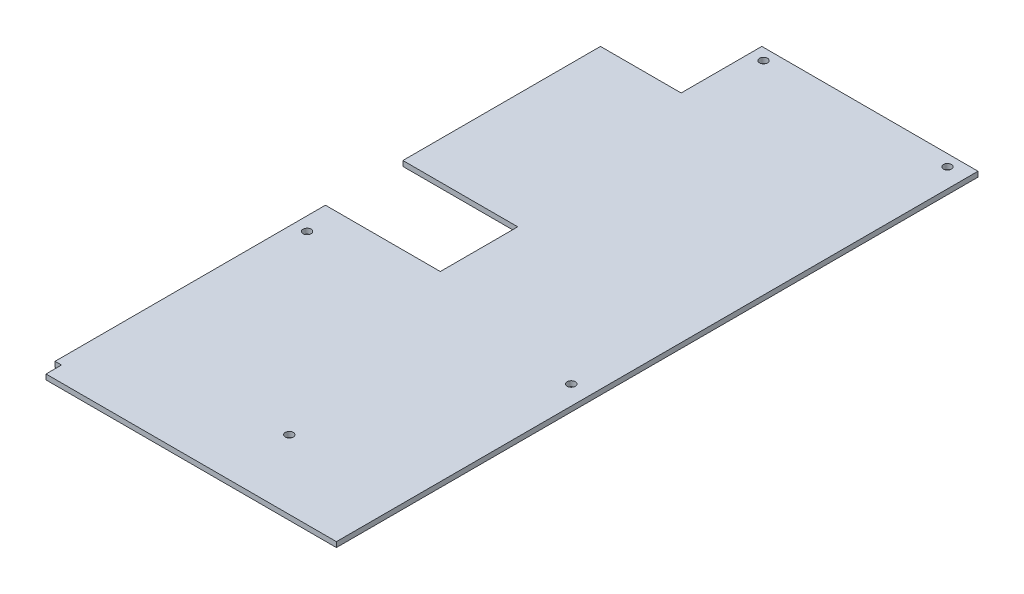
SolidWorks part; units mm, degrees
material "PBT General Purpose"
ref_plane "Front" through (0, 0, 0) normal (0, 0, 1) x (1, 0, 0)
ref_plane "Top" through (0, 0, 0) normal (0, 1, 0) x (1, 0, 0)
ref_plane "Right" through (0, 0, 0) normal (1, 0, 0) x (0, 0, -1)
other "Configuration Table"
sketch "Sketch2" plane through (0, 0, 0) normal (0, 1, 0) x (1, 0, 0)
  line L1 (0, 0) -> (93, 0)
  line L2 (0, 0) -> (0, 198.84)
  line L3 (0, 198.84) -> (93, 198.84)
  line L4 (93, 0) -> (93, 198.84)
  dimension "D1" = 198.84
  dimension "D2" = 93
extrude "Extrude1" add sketch "Sketch2" along normal blind 1.6
sketch "Sketch3" plane through (0, 1.6, 0) normal (0, 1, 0) x (-1, 0, 0)
  line L1 (0, 0) -> (-2, 0)
  line L2 (0, 0) -> (0, -4.8)
  line L3 (0, -4.8) -> (-2, -4.8)
  line L4 (-2, 0) -> (-2, -4.8)
  dimension "D1" = 2
  dimension "D2" = 4.8
extrude "Cut-Extrude1" cut sketch "Sketch3" against normal through all
sketch "Sketch4" plane through (0, 1.6, 0) normal (0, 1, 0) x (-1, 0, 0)
  line L1 (0, -112.6) -> (-35.6, -112.6)
  line L2 (0, -112.6) -> (0, -88.6)
  line L3 (0, -88.6) -> (-35.6, -88.6)
  line L4 (-35.6, -112.6) -> (-35.6, -88.6)
  line L5 (-2, 0) -> (-93, 0) construction
  line L6 (0, -198.84) -> (0, -4.8) construction
  dimension "D1" = 24
  dimension "D2" = 35.6
  dimension "D3" = 88.6
extrude "Cut-Extrude2" cut sketch "Sketch4" against normal through all
sketch "Sketch6" plane through (0, 1.6, 0) normal (0, 1, 0) x (-1, 0, 0)
  line L1 (0, -198.84) -> (-25, -198.84)
  line L2 (0, -198.84) -> (0, -173.84)
  line L3 (0, -173.84) -> (-25, -173.84)
  line L4 (-25, -198.84) -> (-25, -173.84)
  dimension "D1" = 25
  dimension "D2" = 25
extrude "Cut-Extrude3" cut sketch "Sketch6" against normal through all
sketch "Sketch7" plane through (0, 1.6, 0) normal (0, 1, 0) x (-1, 0, 0)
  line L0 (-93, 0) -> (-93, -198.84) construction
  line L1 (-93, -198.84) -> (-25, -198.84) construction
  line L2 (0, -88.6) -> (0, -4.8) construction
  line L3 (-2, 0) -> (-93, 0) construction
  circle A0 centre (-29.077, -195.3) radius 1.25
  circle A1 centre (-86.077, -195.3) radius 1.25
  circle A2 centre (-4.2, -78.7) radius 1.25
  circle A3 centre (-86.077, -78.7) radius 1.25
  dimension "D1" = 2.5
  dimension "D2" = 57
  dimension "D5" = 4.2
  dimension "D7" = 2.5
  dimension "D3" = 6.923
  dimension "D4" = 3.54
  dimension "D6" = 78.7
  dimension "D8" = 78.7
extrude "Cut-Extrude4" cut sketch "Sketch7" against normal through all
sketch "Sketch8" plane through (0, 1.6, 0) normal (0, 1, 0) x (-1, 0, 0)
  line L2 (-93, 0) -> (-93, -198.84) construction
  line L3 (-2, 0) -> (-93, 0) construction
  circle A0 centre (-56, -21.4) radius 1.25
  circle A1 centre (-29.077, -195.3) radius 1.25 construction
  dimension "D1" = 37
  dimension "D2" = 21.4
extrude "Cut-Extrude5" cut sketch "Sketch8" against normal through all
sketch "Sketch10" plane through (0, 0, -198.84) normal (0, 0, -1) x (-1, 0, 0)
  line L0 (-93, 0) -> (-25, 0) construction
  line L1 (-93, 1.6) -> (-92, 1.6)
  line L2 (-93, 1.6) -> (-93, 0)
  line L3 (-93, 0) -> (-92, 0)
  line L4 (-92, 1.6) -> (-92, 0)
  dimension "D1" = 1
extrude "Cut-Extrude6" cut sketch "Sketch10" against normal through all
